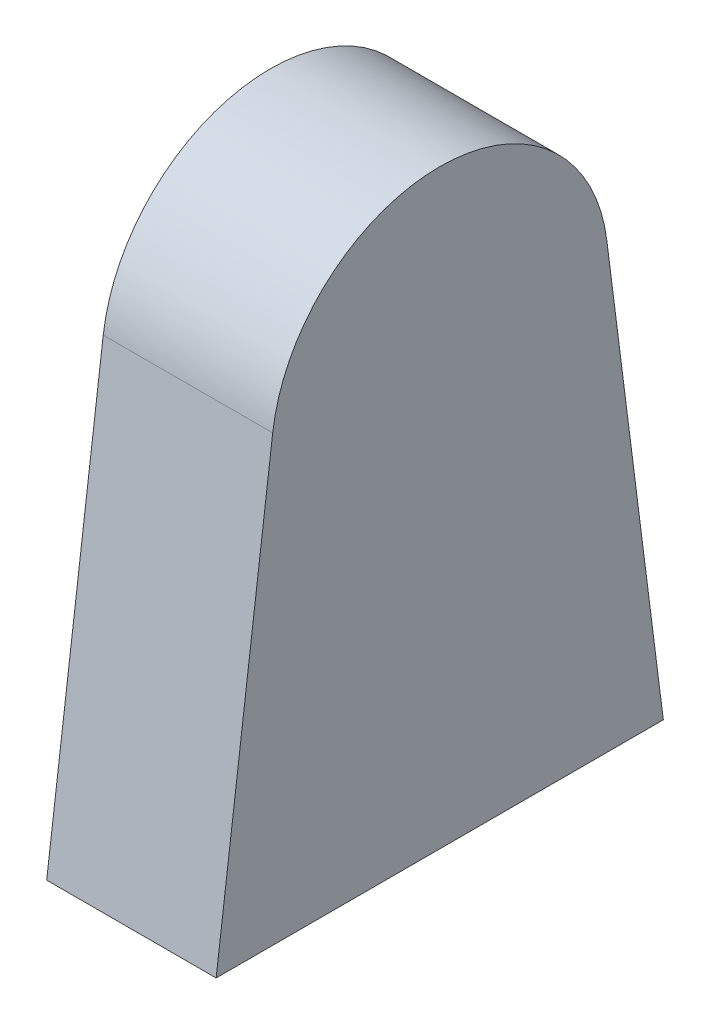
SolidWorks part; units mm, degrees
ref_plane "Front Plane" through (0, 0, 0) normal (0, 0, 1) x (1, 0, 0)
ref_plane "Top Plane" through (0, 0, 0) normal (0, 1, 0) x (1, 0, 0)
ref_plane "Right Plane" through (0, 0, 0) normal (1, 0, 0) x (0, 0, -1)
sketch "Sketch1" plane through (0, 0, 0) normal (1, 0, 0) x (0, 0, -1)
  line L0 (-2.95, 0) -> (2.95, 0) construction
  line L1 (2.95, 0) -> (1.965, 7.7295)
  line L2 (0, 9.46) -> (0, 9.5975) construction
  line L3 (0, 9.5975) -> (0, 0) construction
  line L4 (0, 9.46) -> (3.6602, 9.46) construction
  line L5 (-2.95, 0) -> (-1.965, 7.7295)
  line L7 (3.9581, 0) -> (2.957, 7.8559)
  line L8 (-3.9581, 0) -> (-2.957, 7.8559)
  line L9 (-4.0855, -1) -> (4.0855, -1) construction
  line L10 (-4.0855, -1) -> (-2.957, 7.8559) construction
  line L11 (-2.95, 0) -> (-3.9581, 0)
  line L12 (2.95, 0) -> (3.9581, 0)
  line L13 (4.0855, -1) -> (2.957, 7.8559) construction
  arc A0 (-1.965, 7.7295) -> (1.965, 7.7295) centre (0, 7.4791) cw
  arc A1 (-2.957, 7.8559) -> (2.957, 7.8559) centre (0, 7.4791) cw
  dimension "D1" = 2.95
  dimension "D2" = 1
  dimension "D3" = 1.965
extrude "Boss-Extrude1" add sketch "Sketch1" along normal mid plane 2
sketch "Sketch2" plane through (1, 0, 0) normal (1, 0, 0) x (0, 0, -1)
  line L6 (2.95, 0) -> (3.9581, 0)
  line L7 (3.9581, 0) -> (2.957, 7.8559)
  line L8 (-2.957, 7.8559) -> (-3.9581, 0)
  line L9 (-3.9581, 0) -> (-2.95, 0)
  line L10 (-2.95, 0) -> (-1.965, 7.7295)
  line L11 (1.965, 7.7295) -> (2.95, 0)
  line L12 (2.95, 0) -> (3.9581, 0)
  line L13 (3.9581, 0) -> (2.957, 7.8559)
  line L14 (-2.957, 7.8559) -> (-3.9581, 0)
  line L15 (-3.9581, 0) -> (-2.95, 0)
  line L17 (-2.95, 0) -> (2.95, 0)
  arc A2 (2.957, 7.8559) -> (-2.957, 7.8559) centre (0, 7.4791) ccw
  arc A3 (1.965, 7.7295) -> (-1.965, 7.7295) centre (0, 7.4791) ccw
  arc A4 (2.957, 7.8559) -> (-2.957, 7.8559) centre (0, 7.4791) ccw
  dimension "D1" = 0
extrude "Boss-Extrude2" add sketch "Sketch2" along normal blind 0.5
sketch "Sketch3" plane through (-1, 0, 0) normal (-1, 0, 0) x (0, 0, 1)
  line L3 (-3.9581, 0) -> (3.9581, 0)
  line L4 (-2.957, 7.8559) -> (-3.9581, 0)
  line L5 (3.9581, 0) -> (2.957, 7.8559)
  line L6 (-3.9581, 0) -> (3.9581, 0)
  line L7 (-2.957, 7.8559) -> (-3.9581, 0)
  line L8 (3.9581, 0) -> (2.957, 7.8559)
  arc A1 (2.957, 7.8559) -> (-2.957, 7.8559) centre (0, 7.4791) ccw
  arc A2 (2.957, 7.8559) -> (-2.957, 7.8559) centre (0, 7.4791) ccw
  dimension "D1" = 0
extrude "Boss-Extrude6" add sketch "Sketch3" along normal blind 0.5
